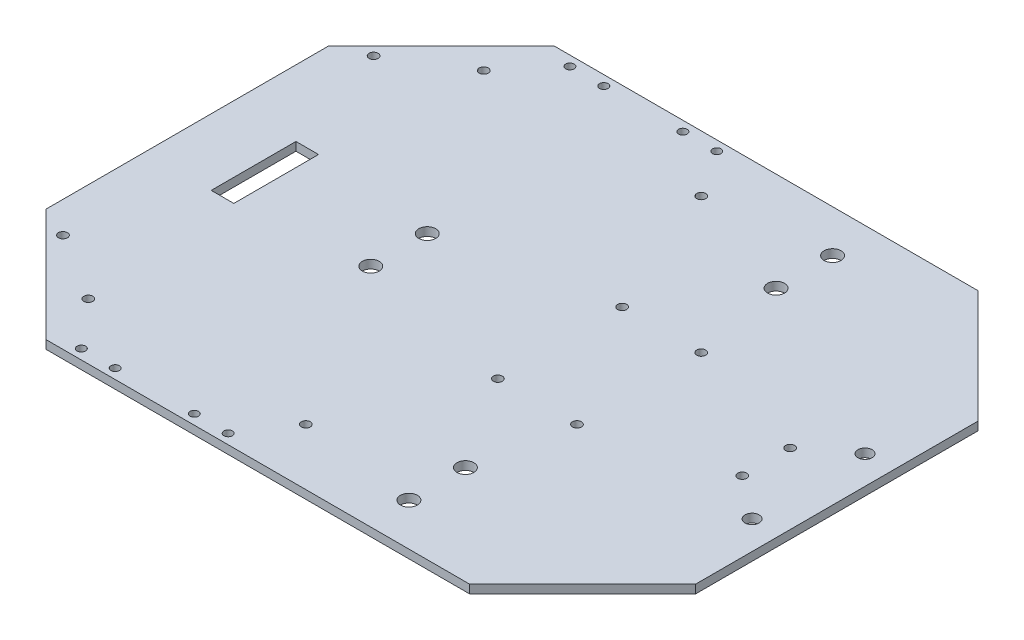
SolidWorks part; units mm, degrees
material "1060 Alloy"
ref_plane "Front Plane" through (0, 0, 0) normal (0, 0, 1) x (1, 0, 0)
ref_plane "Top Plane" through (0, 0, 0) normal (0, 1, 0) x (1, 0, 0)
ref_plane "Right Plane" through (0, 0, 0) normal (1, 0, 0) x (0, 0, -1)
sketch "Sketch3" plane through (0, 0, 0) normal (0, 1, 0) x (1, 0, 0)
  line L0 (-70, 90) -> (80, 90)
  line L2 (120, 50) -> (120, -50)
  line L4 (80, -90) -> (-70, -90)
  line L5 (-110, -50) -> (-70, -90)
  line L6 (-110, -50) -> (-110, 50)
  line L7 (-110, 50) -> (-70, 90)
  line L10 (80, 90) -> (120, 50)
  line L11 (80, -90) -> (120, -50)
  line L20 (-110, 0) -> (120, 0) construction
  circle A0 centre (-99, 55) radius 1.6
  circle A1 centre (-99, -55) radius 1.6
  circle A2 centre (43.5, -55) radius 3
  circle A3 centre (43.5, -75) radius 3
  circle A6 centre (43.5, 75) radius 3
  circle A7 centre (43.5, 55) radius 3
  circle A8 centre (-35, 10) radius 3
  circle A9 centre (-35, -10) radius 3
  circle A12 centre (50, -22) radius 1.6
  circle A17 centre (95, -8.5) radius 1.6
  circle A18 centre (22, 22) radius 1.6
  circle A20 centre (50, 22) radius 1.6
  circle A22 centre (95, 8.5) radius 1.6
  circle A25 centre (22, -22) radius 1.6
  circle A35 centre (-75, -70) radius 1.6
  circle A36 centre (2, -70) radius 1.6
  circle A37 centre (2, 70) radius 1.6
  circle A38 centre (-75, 70) radius 1.6
  dimension "D6" = 100
  dimension "D12" = 20
  dimension "D13" = 75
  dimension "D14" = 110
  dimension "D15" = 11
  dimension "D16" = 15
  dimension "D17" = 20
  dimension "D18" = 35
  dimension "D19" = 20
  dimension "D20" = 77
  dimension "D21" = 76.5
  dimension "D26" = 81.5
  dimension "D30" = 68
  dimension "D31" = 70
  dimension "D32" = 28
  dimension "D33" = 44
  dimension "D51" = 3.2
  dimension "D53" = 3.2
  dimension "D56" = 3.2
  dimension "D58" = 3.2
  dimension "D10" = 25
  dimension "D11" = 6
  dimension "D2" = 180
  dimension "D7" = 120
  dimension "D8" = 110
  dimension "D9" = 40
  dimension "D37" = 40
  dimension "D38" = 40
  dimension "D39" = 40
  dimension "D40" = 40
extrude "Boss-Extrude1" add sketch "Sketch3" along normal blind 3
sketch "Sketch6" plane through (0, 0, 0) normal (0, -1, 0) x (-1, 0, 0)
  line L0 (110, 50) -> (110, -50) construction
  line L1 (90, -45) -> (50, -45)
  line L2 (90, -45) -> (90, 45)
  line L3 (90, 45) -> (50, 45)
  line L4 (50, -45) -> (50, 45)
  circle A0 centre (84, -39) radius 2.2
  circle A1 centre (84, 39) radius 2.2
  circle A2 centre (56, 39) radius 2.2
  circle A3 centre (56, -39) radius 2.2
  point P16 (50, 0)
  dimension "D2" = 20
  dimension "D4" = 4.4
  dimension "D5" = 6
  dimension "D6" = 6
  dimension "D7" = 6
  dimension "D8" = 6
  dimension "D1" = 40
  dimension "D3" = 90
sketch "Sketch8" plane through (0, 0, 0) normal (0, -1, 0) x (1, 0, 0)
  line L0 (80, -90) -> (-70, -90) construction
  line L1 (-110, -50) -> (-110, 50) construction
  circle A0 centre (-21, -86.5) radius 1.25
  circle A1 centre (-49, -86.5) radius 1.25
  dimension "D1" = 3.5
  dimension "D2" = 2.5
  dimension "D3" = 28
  dimension "D4" = 61
hole_wizard "Ø3.0mm Dowel Hole1" positions "3DSketch1" profile "Sketch9" hole size "Ø3.0" standard "ISO"
sketch3d "3DSketch1"
  point P0 (-21, 0, -86.5)
  point P3 (-49, 0, -86.5)
sketch "Sketch9" plane through (-21, 0, -86.5) normal (1, 0, 0) x (0, 0, -1)
  line L0 (0, 0) -> (0, 5.9013)
  line L1 (0, 5.9013) -> (1.5, 5)
  line L2 (1.5, 5) -> (1.5, 0)
  line L5 (1.5, 0) -> (0, 0)
  line L10 (0, 5.9013) -> (-1.5, 5) construction
  line L11 (0, -6.35) -> (0, 107.95) construction
  dimension "Hole Dia." = 3
  dimension "Hole Depth" = 5
  dimension "Drill Angle" = 118
mirror "Mirror3" about plane through (0, 0, 0) normal (0, 0, 1) of "Ø3.0mm Dowel Hole1"
sketch "Sketch10" plane through (0, 0, 0) normal (0, -1, 0) x (1, 0, 0)
  line L0 (-70, 90) -> (80, 90) construction
  line L1 (120, 50) -> (120, -50) construction
  circle A0 centre (110, -20) radius 2.1
  circle A1 centre (110, 20) radius 2.1
  dimension "D1" = 4.2
  dimension "D2" = 40
  dimension "D3" = 110
  dimension "D4" = 10
hole_wizard "Ø5.0mm Dowel Hole1" positions "3DSketch2" profile "Sketch11" hole size "Ø5.0" standard "ISO"
sketch3d "3DSketch2"
  point P0 (110, 0, -20)
  point P3 (110, 0, 20)
sketch "Sketch11" plane through (110, 0, -20) normal (1, 0, 0) x (0, 0, -1)
  line L0 (0, 0) -> (0, 6.5022)
  line L1 (0, 6.5022) -> (2.5, 5)
  line L2 (2.5, 5) -> (2.5, 0)
  line L5 (2.5, 0) -> (0, 0)
  line L10 (0, 6.5022) -> (-2.5, 5) construction
  line L11 (0, -6.35) -> (0, 107.95) construction
  dimension "Hole Dia." = 5
  dimension "Hole Depth" = 5
  dimension "Drill Angle" = 118
sketch "Sketch12" plane through (0, 3, 0) normal (0, 1, 0) x (1, 0, 0)
  line L1 (-110, 50) -> (-110, -50) construction
  line L2 (-70, -90) -> (80, -90) construction
  line L3 (0, 0) -> (-110, 0) construction
  circle A0 centre (-61, -86.5) radius 1.5
  circle A1 centre (-9, -86.5) radius 1.5
  circle A2 centre (-61, 86.5) radius 1.5
  circle A3 centre (-9, 86.5) radius 1.5
  dimension "D1" = 49
  dimension "D2" = 52
  dimension "D3" = 3
  dimension "D4" = 3.5
extrude "Cut-Extrude1" cut sketch "Sketch12" against normal through all
sketch "Sketch13" plane through (0, 0, 0) normal (0, -1, 0) x (-1, 0, 0)
  line L0 (110, 50) -> (110, -50) construction
  line L1 (86.5, -15) -> (78.5, -15)
  line L2 (86.5, -15) -> (86.5, 15)
  line L3 (86.5, 15) -> (78.5, 15)
  line L4 (78.5, -15) -> (78.5, 15)
  point P8 (78.5, 0)
  dimension "D1" = 23.5
  dimension "D2" = 8
  dimension "D3" = 30
extrude "Cut-Extrude2" cut sketch "Sketch13" against normal up to surface (3 mm away) up to face at (-9, 3, 88)
